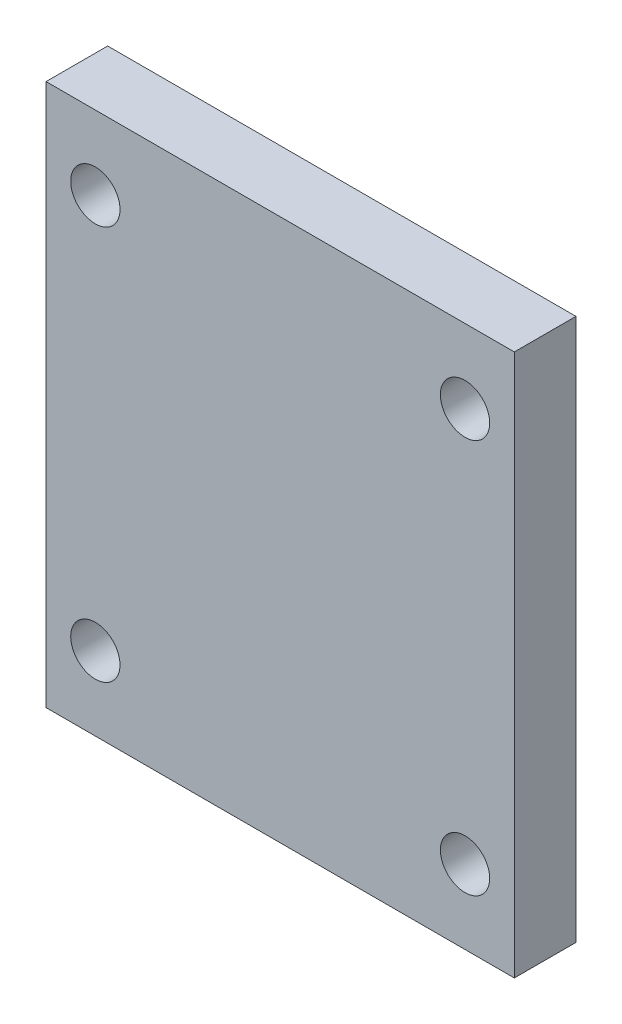
SolidWorks part; units mm, degrees
ref_plane "Front Plane" through (0, 0, 0) normal (0, 0, 1) x (1, 0, 0)
ref_plane "Top Plane" through (0, 0, 0) normal (0, 1, 0) x (1, 0, 0)
ref_plane "Right Plane" through (0, 0, 0) normal (1, 0, 0) x (0, 0, -1)
sketch "Sketch1" plane through (0, 0, 0) normal (0, 0, 1) x (1, 0, 0)
  line L1 (-19, -22) -> (19, -22)
  line L2 (-19, -22) -> (-19, 22)
  line L3 (-19, 22) -> (19, 22)
  line L4 (19, -22) -> (19, 22)
  circle A0 centre (-15, 16) radius 2
  circle A1 centre (-15, -16) radius 2
  circle A2 centre (15, -16) radius 2
  circle A3 centre (15, 16) radius 2
  point P0 (0, 0)
  dimension "D1" = 4
  dimension "D2" = 15
  dimension "D3" = 19
  dimension "D4" = 15
  dimension "D5" = 19
  dimension "D6" = 16
  dimension "D7" = 22
  dimension "D8" = 16
  dimension "D9" = 22
extrude "Boss-Extrude1" add sketch "Sketch1" along normal mid plane 5
